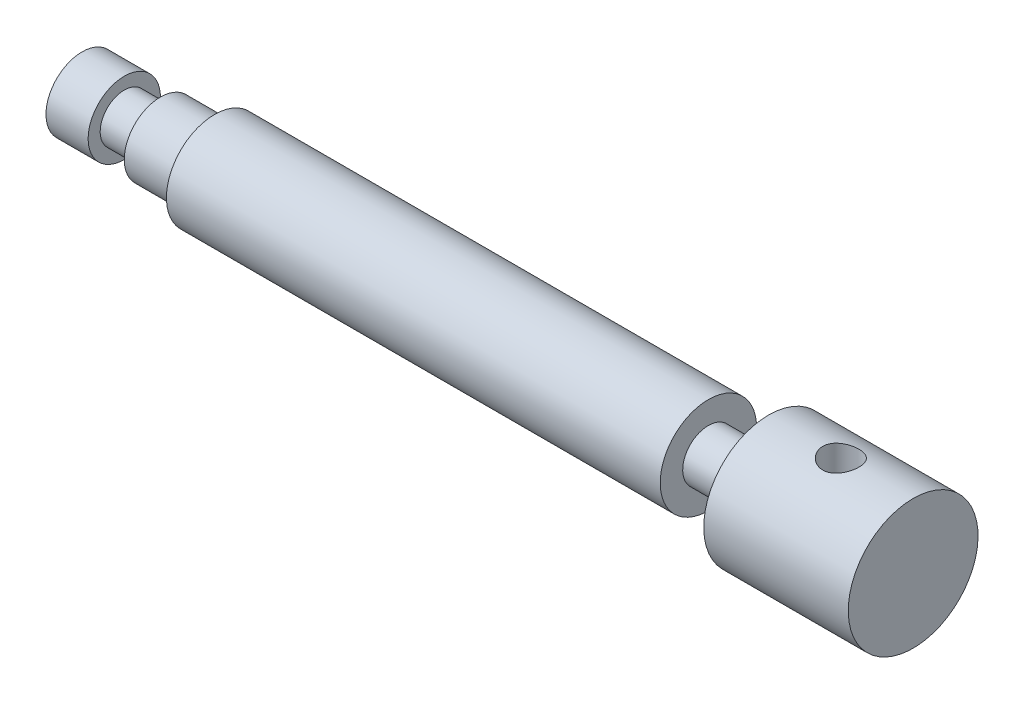
SolidWorks part; units mm, degrees
material "AISI 347 Annealed Stainless Steel (SS)"
ref_plane "Front Plane" through (0, 0, 0) normal (0, 0, 1) x (1, 0, 0)
ref_plane "Top Plane" through (0, 0, 0) normal (0, 1, 0) x (1, 0, 0)
ref_plane "Right Plane" through (0, 0, 0) normal (1, 0, 0) x (0, 0, -1)
sketch "Sketch1" plane through (0, 0, 0) normal (0, 0, 1) x (1, 0, 0)
  line L0 (41, 4.2679) -> (51, 4.2679)
  line L1 (-41, 8) -> (41, 8)
  line L2 (41, 8) -> (41, 4.2679)
  line L3 (-41, 6) -> (-50, 6)
  line L4 (-41, 8) -> (-41, 6)
  line L5 (41, 8) -> (-41, -8) construction
  line L6 (0, 0) -> (-41, 8) construction
  line L7 (51, 4.2679) -> (51, 10.7746)
  line L8 (51, 10.7746) -> (75, 10.7746)
  line L9 (75, 10.7746) -> (75, 0)
  line L10 (1088.6664, 0) -> (75, 0) construction
  line L11 (75, 0) -> (-63, 0)
  line L12 (0, 0) -> (0, 50000) construction
  line L13 (-63, 2.7493) -> (-63, -49997.2507) construction
  line L14 (-63, 0) -> (-63, 6)
  line L15 (-63, 6) -> (-56, 6)
  line L17 (-56, 6) -> (-56, 4)
  line L18 (-56, 4) -> (-50, 4)
  line L19 (-50, 4) -> (-50, 6)
  line L20 (-63, 0) -> (-1063.5868, 0) construction
  point P0 (0, 0)
  dimension "D1" = 138
  dimension "D2" = 16
  dimension "D3" = 10
  dimension "D4" = 24
  dimension "D5" = 6
  dimension "D6" = 7
  dimension "D7" = 6
  dimension "D8" = 82
  dimension "D9" = 3.7321
  dimension "D10" = 41
  dimension "D11" = 8
revolve "Revolve1" add sketch "Sketch1" angle 360 about L11
ref_plane "Plane1" through (0, 10.7746, 0) normal (0, 1, 0) x (1, 0, 0)
sketch "Sketch2" plane through (0, 10.7746, 0) normal (0, 1, 0) x (1, 0, 0)
  line L0 (75, 0) -> (50075, 0) construction
  line L1 (75, -10.7746) -> (75, 10.7746) construction
  line L2 (51, 0) -> (51, 50000) construction
  line L3 (51, 4.2679) -> (51, -4.2679) construction
  circle A0 centre (63, 0) radius 3
  point P4 (75, 0)
  point P9 (51, 0)
  dimension "D1" = 6
  dimension "D2" = 12
extrude "Cut-Extrude1" cut sketch "Sketch2" against normal through all both and the other way through all
